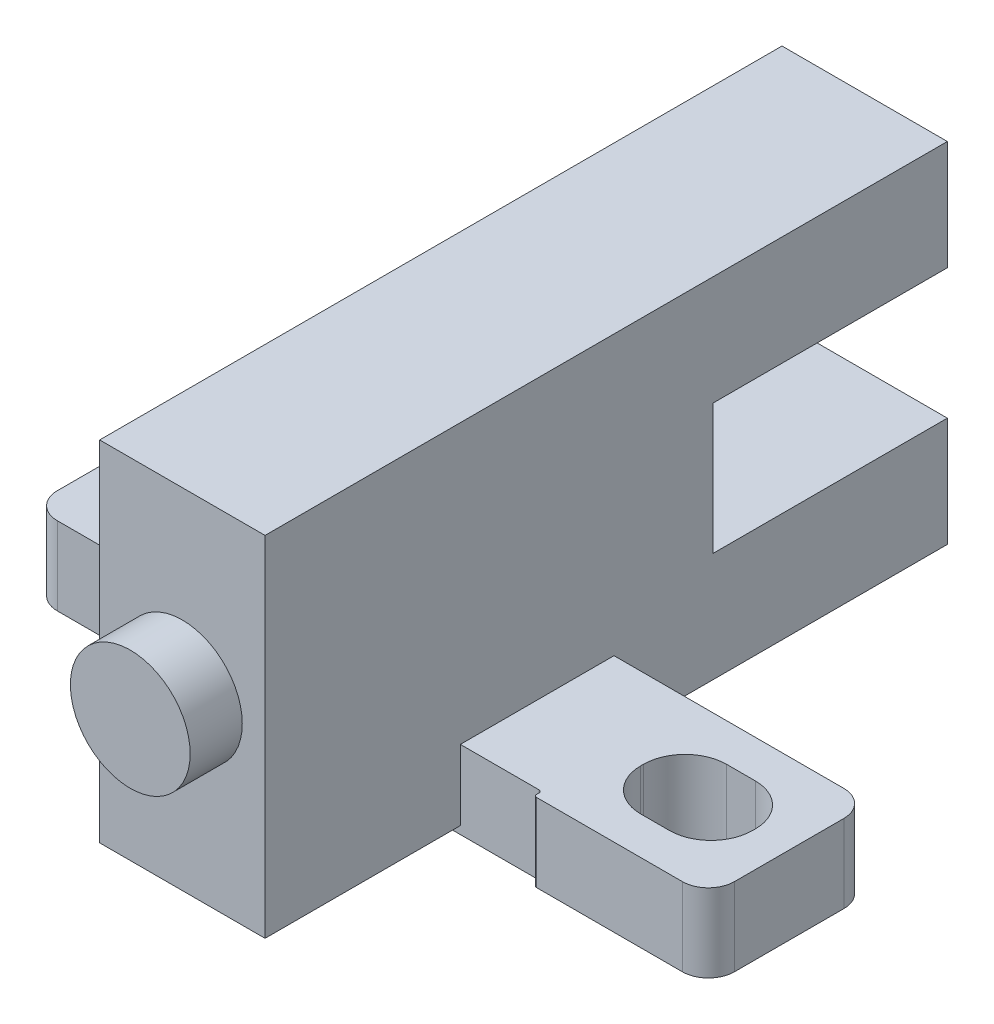
SolidWorks part; units mm, degrees
ref_plane "前视基准面" through (0, 0, 0) normal (0, 0, 1) x (1, 0, 0)
ref_plane "上视基准面" through (0, 0, 0) normal (0, 1, 0) x (1, 0, 0)
ref_plane "右视基准面" through (0, 0, 0) normal (1, 0, 0) x (0, 0, -1)
sketch "草图1" plane through (0, 0, 0) normal (0, 1, 0) x (1, 0, 0)
  line L0 (-19.5085, 0) -> (20.5378, 0) construction
  line L1 (-13, 2.1) -> (-13, -2.1)
  line L3 (13, 2.1) -> (13, -2.1)
  line L4 (0, 28.6041) -> (0, -32.8052) construction
  line L5 (-12, 3.1) -> (12, 3.1)
  line L6 (10.05, 1.65) -> (8.95, 1.65)
  line L7 (-10.05, 1.65) -> (-8.95, 1.65)
  line L8 (-11.65, 0.05) -> (-11.65, -0.05)
  line L9 (-10.05, -1.65) -> (-8.95, -1.65)
  line L10 (-7.35, 0.05) -> (-7.35, -0.05)
  line L11 (-11.65, 1.65) -> (-7.35, -1.65) construction
  line L12 (-11.65, -1.65) -> (-7.35, 1.65) construction
  line L13 (7.35, 0.05) -> (7.35, -0.05)
  line L14 (10.05, -1.65) -> (8.95, -1.65)
  line L15 (11.65, 0.05) -> (11.65, -0.05)
  line L16 (-12, -3.1) -> (-6.4, -3.1)
  line L17 (-6.3, -3) -> (-6.3, -2.9)
  line L18 (-6.2, -2.8) -> (6.2, -2.8)
  line L19 (12, -3.1) -> (6.4, -3.1)
  line L20 (6.3, -3) -> (6.3, -2.9)
  arc A0 (13, -2.1) -> (12, -3.1) centre (12, -2.1) cw
  arc A1 (-13, -2.1) -> (-12, -3.1) centre (-12, -2.1) ccw
  arc A2 (-13, 2.1) -> (-12, 3.1) centre (-12, 2.1) cw
  arc A3 (13, 2.1) -> (12, 3.1) centre (12, 2.1) ccw
  arc A4 (-8.95, 1.65) -> (-7.35, 0.05) centre (-8.95, 0.05) cw
  arc A5 (-8.95, -1.65) -> (-7.35, -0.05) centre (-8.95, -0.05) ccw
  arc A6 (-11.65, -0.05) -> (-10.05, -1.65) centre (-10.05, -0.05) ccw
  arc A7 (-10.05, 1.65) -> (-11.65, 0.05) centre (-10.05, 0.05) ccw
  arc A8 (8.95, 1.65) -> (7.35, 0.05) centre (8.95, 0.05) ccw
  arc A9 (8.95, -1.65) -> (7.35, -0.05) centre (8.95, -0.05) cw
  arc A10 (11.65, -0.05) -> (10.05, -1.65) centre (10.05, -0.05) cw
  arc A11 (10.05, 1.65) -> (11.65, 0.05) centre (10.05, 0.05) cw
  arc A12 (-6.4, -3.1) -> (-6.3, -3) centre (-6.4, -3) ccw
  arc A13 (6.4, -3.1) -> (6.3, -3) centre (6.4, -3) cw
  arc A14 (6.3, -2.9) -> (6.2, -2.8) centre (6.2, -2.9) ccw
  arc A15 (-6.3, -2.9) -> (-6.2, -2.8) centre (-6.2, -2.9) cw
  point P10 (0, -3.1)
  point P12 (13, -3.1)
  point P15 (-13, -3.1)
  point P17 (13, 0)
  point P18 (-13, 0)
  point P22 (-13, 3.1)
  point P23 (13, 3.1)
  point P24 (0, 3.1)
  point P25 (-9.5, 0)
  point P59 (0, -2.8)
  point P61 (-6.3, -3.1)
  point P64 (6.3, -3.1)
  point P67 (6.3, -2.8)
  point P70 (-6.3, -2.8)
  dimension "D3" = 1
  dimension "D5" = 19
  dimension "D7" = 1.6
  dimension "D10" = 0.1
  dimension "D1" = 26
  dimension "D2" = 0.3
  dimension "D4" = 4.3
  dimension "D6" = 3.3
  dimension "D8" = 12.6
  dimension "D9" = 6.2
extrude "凸台-拉伸1" add sketch "草图1" along normal mid plane 3
sketch "草图8" plane through (0, 0, 0) normal (1, 0, 0) x (0, 0, -1)
  line L0 (-9.4101, 5.5) -> (11.2656, 5.5) construction
  line L1 (6.9, 3) -> (6.9, 8)
  line L2 (6.9, 8) -> (15.9, 8)
  line L3 (15.9, 8) -> (15.9, 12.2)
  line L4 (15.9, 12.2) -> (-10.3, 12.2)
  line L5 (-10.3, 12.2) -> (-10.3, -1.2)
  line L6 (-2.1, -1.5) -> (2.1, -1.5) construction
  line L7 (0, 8.6456) -> (0, -11.1649) construction
  line L8 (15.9, -1.2) -> (-10.3, -1.2)
  line L9 (15.9, 3) -> (15.9, -1.2)
  line L10 (6.9, 3) -> (15.9, 3)
  point P14 (-10.3, 5.5)
  point P17 (6.9, 5.5)
  dimension "D1" = 13.4
  dimension "D2" = 13.7
  dimension "D3" = 5
  dimension "D4" = 26.2
  dimension "D5" = 10.3
  dimension "D6" = 9
extrude "凸台-拉伸2" add sketch "草图8" along normal mid plane 6.35
sketch "草图9" plane through (0, 0, 10.3) normal (0, 0, 1) x (1, 0, 0)
  line L0 (-3.175, 12.2) -> (3.175, -1.2) construction
  line L1 (3.175, 12.2) -> (-3.175, -1.2) construction
  circle A0 centre (0, 5.5) radius 2.3
  dimension "D1" = 4.6
extrude "凸台-拉伸3" add sketch "草图9" along normal blind 2
